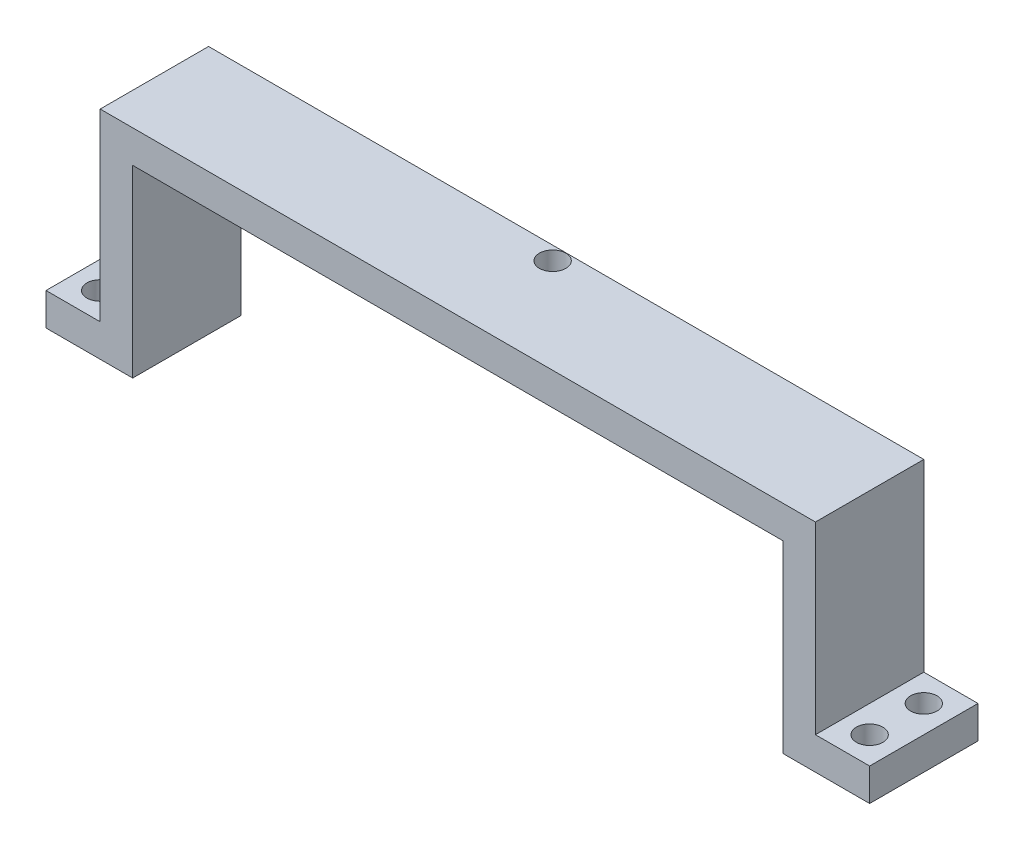
SolidWorks part; units mm, degrees
ref_plane "Front Plane" through (0, 0, 0) normal (0, 0, 1) x (1, 0, 0)
ref_plane "Top Plane" through (0, 0, 0) normal (0, 1, 0) x (1, 0, 0)
ref_plane "Right Plane" through (0, 0, 0) normal (1, 0, 0) x (0, 0, -1)
sketch "Sketch1" plane through (0, 0, 0) normal (0, 1, 0) x (1, 0, 0)
  line L0 (33, 0) -> (-33, 0)
  line L1 (-33, -5) -> (-33, 5)
  line L2 (-33, 5) -> (33, 5)
  line L3 (33, 5) -> (33, -5)
  line L4 (33, -5) -> (-33, -5)
  point P4 (0, 0)
  point P7 (-33, 0)
extrude "Boss-Extrude1" add sketch "Sketch1" along normal blind 3 contours L3 L2 L1 L0 | L4 L3 L0 L1
sketch "Sketch3" plane through (0, 0, 0) normal (0, -1, 0) x (1, 0, 0)
  line L0 (-33, -5) -> (-30, -5)
  line L1 (-33, -5) -> (33, -5) construction
  line L2 (-30, -5) -> (-30, 5)
  line L3 (33, 5) -> (-33, 5) construction
  line L4 (-30, 5) -> (-33, 5)
  line L5 (-33, 5) -> (-33, -5)
  line L6 (33, -5) -> (30, -5)
  line L7 (30, -5) -> (30, 5)
  line L8 (30, 5) -> (33, 5)
  line L9 (33, -5) -> (33, 5) construction
  line L10 (33, 5) -> (33, -5)
extrude "Boss-Extrude2" add sketch "Sketch3" along normal blind 14
sketch "Sketch4" plane through (0, -14, 0) normal (0, -1, 0) x (1, 0, 0)
  line L0 (-30, -5) -> (-30, 5)
  line L1 (-30, 5) -> (-33, 5) construction
  line L2 (-30, -5) -> (-30, 5) construction
  line L3 (-30, 5) -> (-38, 5)
  line L4 (-38, 5) -> (-38, -5)
  line L5 (-38, -5) -> (-30, -5)
  line L6 (30, -5) -> (38, -5)
  line L7 (38, -5) -> (38, 5)
  line L8 (38, 5) -> (30, 5)
  line L9 (30, 5) -> (30, -5)
  line L10 (30, -5) -> (30.0498, -4.8503)
extrude "Boss-Extrude3" add sketch "Sketch4" along normal blind 3
sketch "Sketch5" plane through (0, 3, 0) normal (0, 1, 0) x (1, 0, 0)
  line L0 (-33, 5) -> (33, 5) construction
  circle A0 centre (0, 3.75) radius 1.22
  dimension "D1" = 1.25
extrude "Cut-Extrude1" cut sketch "Sketch5" against normal through all
sketch "Sketch6" plane through (0, -14, 0) normal (0, 1, 0) x (1, 0, 0)
  line L0 (-33, -5) -> (-38, -5) construction
  line L1 (-38, 5) -> (-33, 5) construction
  line L2 (-38, -5) -> (-38, 5) construction
  circle A0 centre (-35.5, -2.5) radius 1.22
  circle A1 centre (-35.5, 2.5) radius 1.22
  dimension "D1" = 2.5
  dimension "D2" = 2.5
  dimension "D3" = 2.5
  dimension "D4" = 2.5
extrude "Cut-Extrude2" cut sketch "Sketch6" against normal through all
mirror "Mirror1" about plane through (0, 0, 0) normal (1, 0, 0) of "Cut-Extrude2"
